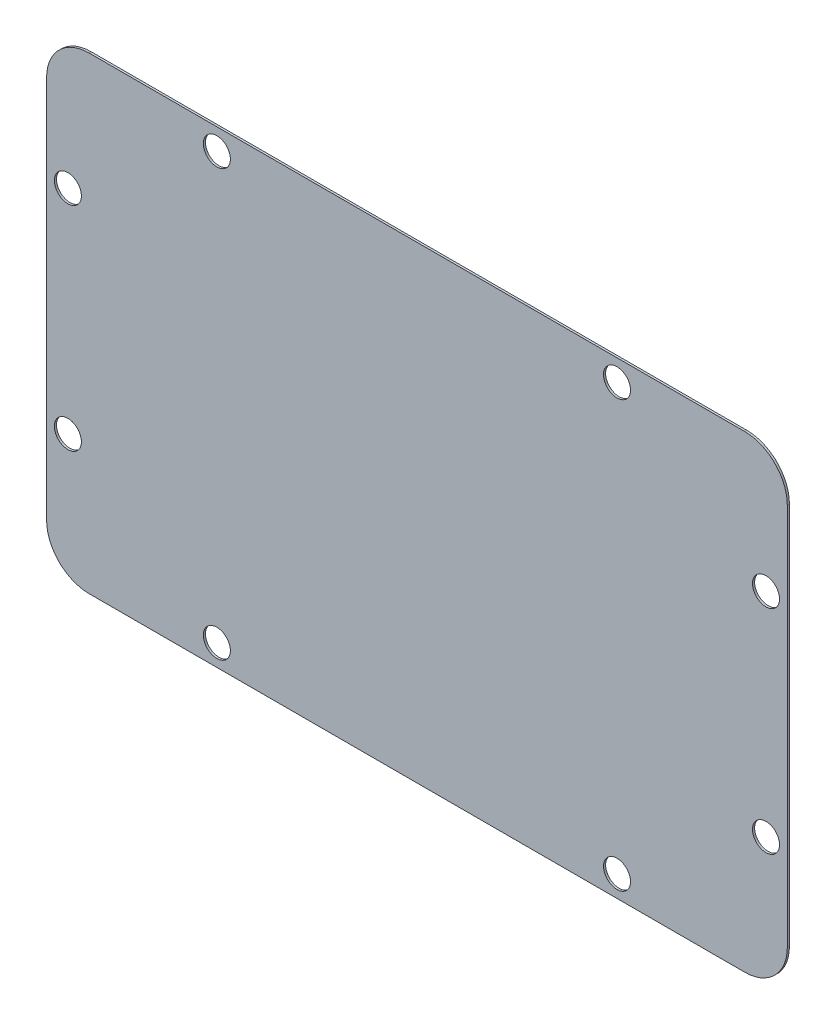
SolidWorks part; units mm, degrees
material "AISI 304"
ref_plane "Plano frontal" through (0, 0, 0) normal (0, 0, 1) x (1, 0, 0)
ref_plane "Plano superior" through (0, 0, 0) normal (0, 1, 0) x (1, 0, 0)
ref_plane "Plano direito" through (0, 0, 0) normal (1, 0, 0) x (0, 0, -1)
sketch "Esboço1" plane through (0, 0, 0) normal (0, 0, 1) x (1, 0, 0)
  line L1 (-10, 0) -> (-164, 0)
  line L2 (0, 10) -> (0, 100)
  line L3 (-10, 110) -> (-164, 110)
  line L4 (-174, 10) -> (-174, 100)
  arc A0 (-10, 0) -> (0, 10) centre (-10, 10) ccw
  arc A1 (-164, 0) -> (-174, 10) centre (-164, 10) cw
  arc A2 (0, 100) -> (-10, 110) centre (-10, 100) ccw
  arc A3 (-164, 110) -> (-174, 100) centre (-164, 100) ccw
  point P7 (0, 0)
  point P10 (-174, 0)
  point P15 (-174, 110)
  dimension "D3" = 10
  dimension "D1" = 174
  dimension "D2" = 110
extrude "Ressalto-extrusão1" add sketch "Esboço1" along normal blind 0.5
hole_wizard "Broca de rosquear para tarraxa de M3x0.51" positions "Esboço2" profile "Esboço3" hole size "M3x0.5" standard "Ansi Metric"
sketch "Esboço2" plane through (0, 0, 0.5) normal (0, 0, 1) x (1, 0, 0)
  line L0 (-10, 110) -> (-164, 110) construction
  line L1 (-174, 100) -> (-174, 10) construction
  line L2 (-164, 0) -> (-10, 0) construction
  line L3 (0, 10) -> (0, 100) construction
  point P0 (-169, 80)
  point P2 (-134, 105)
  point P4 (-40, 105)
  point P6 (-5, 80)
  point P8 (-5, 30)
  point P10 (-169, 30)
  point P12 (-134, 5)
  point P14 (-40, 5)
  dimension "D1" = 5
  dimension "D2" = 5
  dimension "D3" = 5
  dimension "D4" = 5
  dimension "D5" = 40
  dimension "D6" = 40
  dimension "D7" = 30
  dimension "D8" = 30
sketch "Esboço3" plane through (-169, 80, 0.5) normal (1, 0, 0) x (0, -1, 0)
  line L0 (0, 0) -> (0, 25.4)
  line L1 (0, 25.4) -> (3.175, 23.4923)
  line L2 (3.175, 23.4923) -> (3.175, 0)
  line L5 (3.175, 0) -> (0, 0)
  line L10 (0, 25.4) -> (-3.175, 23.4923) construction
  line L11 (0, -6.35) -> (0, 107.95) construction
  dimension "Hole Dia." = 6.35
  dimension "Hole Depth" = 25.4
  dimension "Drill Angle" = 118
